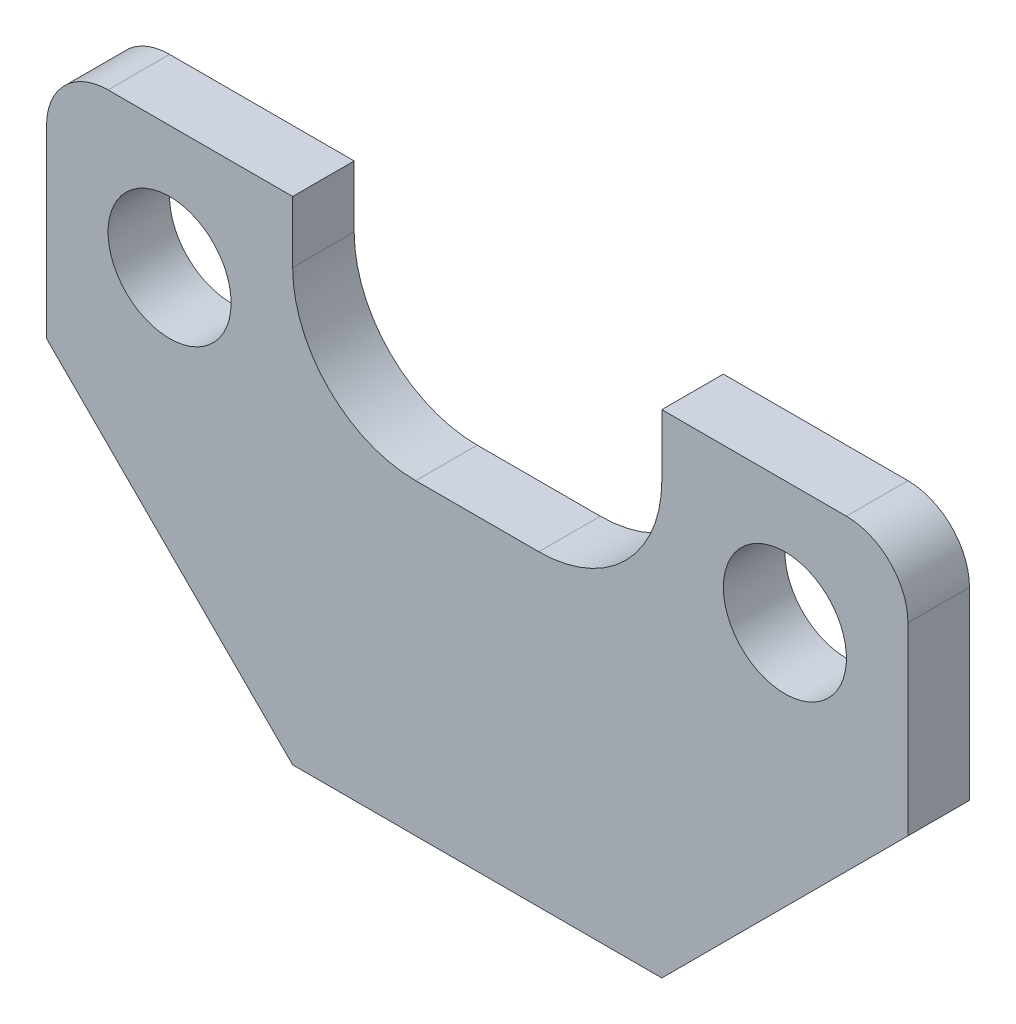
SolidWorks part; units mm, degrees
ref_plane "Front Plane" through (0, 0, 0) normal (0, 0, 1) x (1, 0, 0)
ref_plane "Top Plane" through (0, 0, 0) normal (0, 1, 0) x (1, 0, 0)
ref_plane "Right Plane" through (0, 0, 0) normal (1, 0, 0) x (0, 0, -1)
sketch "Sketch1" plane through (0, 0, 0) normal (0, 0, 1) x (1, 0, 0)
  line L2 (0, 0) -> (30, 0)
  line L3 (0, 0) -> (-20, 20)
  line L4 (-20, 20) -> (-20, 40)
  line L5 (-20, 40) -> (0, 40)
  line L6 (-10, 65.3333) -> (-10, 20) construction
  line L7 (-27.413, 30) -> (11.3749, 30) construction
  line L8 (15, 71.7393) -> (15, -17.943) construction
  line L9 (0, 40) -> (0, 35)
  line L10 (10, 25) -> (20, 25)
  line L11 (30, 0) -> (50, 20)
  line L12 (50, 20) -> (50, 40)
  line L13 (50, 40) -> (30, 40)
  line L14 (30, 40) -> (30, 35)
  circle A0 centre (-10, 30) radius 5
  arc A3 (0, 35) -> (10, 25) centre (10, 35) ccw
  arc A4 (30, 35) -> (20, 25) centre (20, 35) cw
  circle A5 centre (40, 30) radius 5
  point P18 (15, 0)
  point P20 (15, 25)
  dimension "D6" = 10
  dimension "D1" = 20
  dimension "D2" = 10
  dimension "D3" = 15
  dimension "D4" = 40
  dimension "D5" = 10
extrude "Boss-Extrude1" add sketch "Sketch1" along normal blind 5
fillet "Fillet1" radius 5 2 edges at (50, 40, 2.5) (-20, 40, 2.5)
